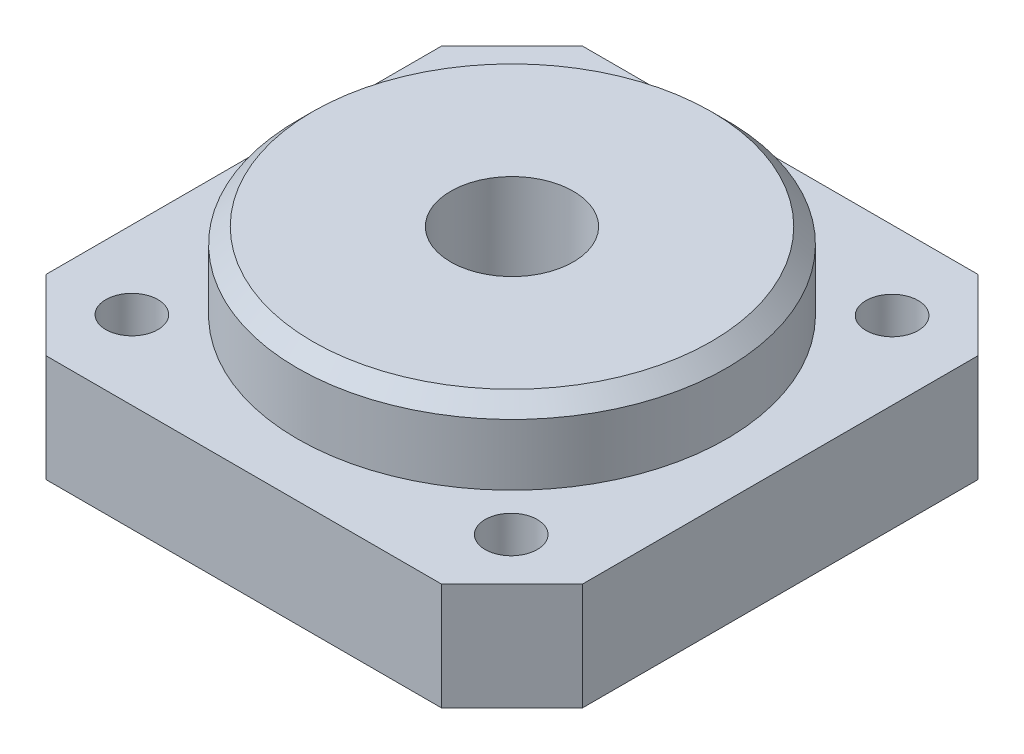
SolidWorks part; units mm, degrees
ref_plane "Front" through (0, 0, 0) normal (0, 0, 1) x (1, 0, 0)
ref_plane "Top" through (0, 0, 0) normal (0, 1, 0) x (1, 0, 0)
ref_plane "Right" through (0, 0, 0) normal (1, 0, 0) x (0, 0, -1)
sketch "草图1" plane through (0, 0, 0) normal (0, 1, 0) x (1, 0, 0)
  line L0 (-26.2497, 0) -> (26.3548, 0) construction
  line L1 (0, 27.8421) -> (0, -27.6638) construction
  line L2 (0, 17.5) -> (12.9056, 17.5)
  line L3 (12.9056, 17.5) -> (17.5, 12.9056)
  line L4 (17.5, 12.9056) -> (17.5, 0)
  line L5 (0.0525, 0) -> (25.3889, 25.3363) construction
  line L6 (17.5, 0) -> (17.5, -12.9056)
  line L7 (17.5, -12.9056) -> (12.9056, -17.5)
  line L8 (12.9056, -17.5) -> (0, -17.5)
  line L9 (0, -17.5) -> (-12.9056, -17.5)
  line L10 (-12.9056, -17.5) -> (-17.5, -12.9056)
  line L11 (-17.5, -12.9056) -> (-17.5, 0)
  line L12 (-17.5, 0) -> (-17.5, 12.9056)
  line L13 (-17.5, 12.9056) -> (-12.9056, 17.5)
  line L14 (-12.9056, 17.5) -> (0, 17.5)
  circle A0 centre (12.4269, 12.3744) radius 1.7
  circle A1 centre (12.3744, -12.4269) radius 1.7
  circle A2 centre (-12.4269, -12.3744) radius 1.7
  circle A3 centre (-12.3744, 12.4269) radius 1.7
  point P34 (0, 0)
  dimension "D5" = 3.4
  dimension "D1" = 17.5
  dimension "D2" = 17.5
  dimension "D3" = 135
  dimension "D4" = 21.5
  dimension "D6" = 17.5
  dimension "D7" = 4
extrude "凸台-拉伸1" add sketch "草图1" along normal blind 7
sketch "草图2" plane through (0, 7, 0) normal (0, 1, 0) x (1, 0, 0)
  circle A0 centre (0, 0) radius 14
  dimension "D1" = 28
extrude "凸台-拉伸2" add sketch "草图2" along normal blind 5
sketch "草图3" plane through (0, 12, 0) normal (0, 1, 0) x (1, 0, 0)
  circle A0 centre (0, 0) radius 4
  dimension "D1" = 8
extrude "切除-拉伸1" cut sketch "草图3" against normal up to next
sketch "草图4" plane through (0, 0, 0) normal (0, -1, 0) x (1, 0, 0)
  circle A0 centre (-12.4269, 12.3744) radius 3.25
  circle A1 centre (12.3744, 12.4269) radius 3.25
  circle A2 centre (12.4269, -12.3744) radius 3.25
  circle A3 centre (-12.3744, -12.4269) radius 3.25
  point P12 (0, 0)
  dimension "D1" = 6.5
  dimension "D2" = 4
extrude "切除-拉伸2" cut sketch "草图4" against normal blind 4
chamfer "倒角1" distance 1 angle 45 1 edges at (0, 12, 14)
